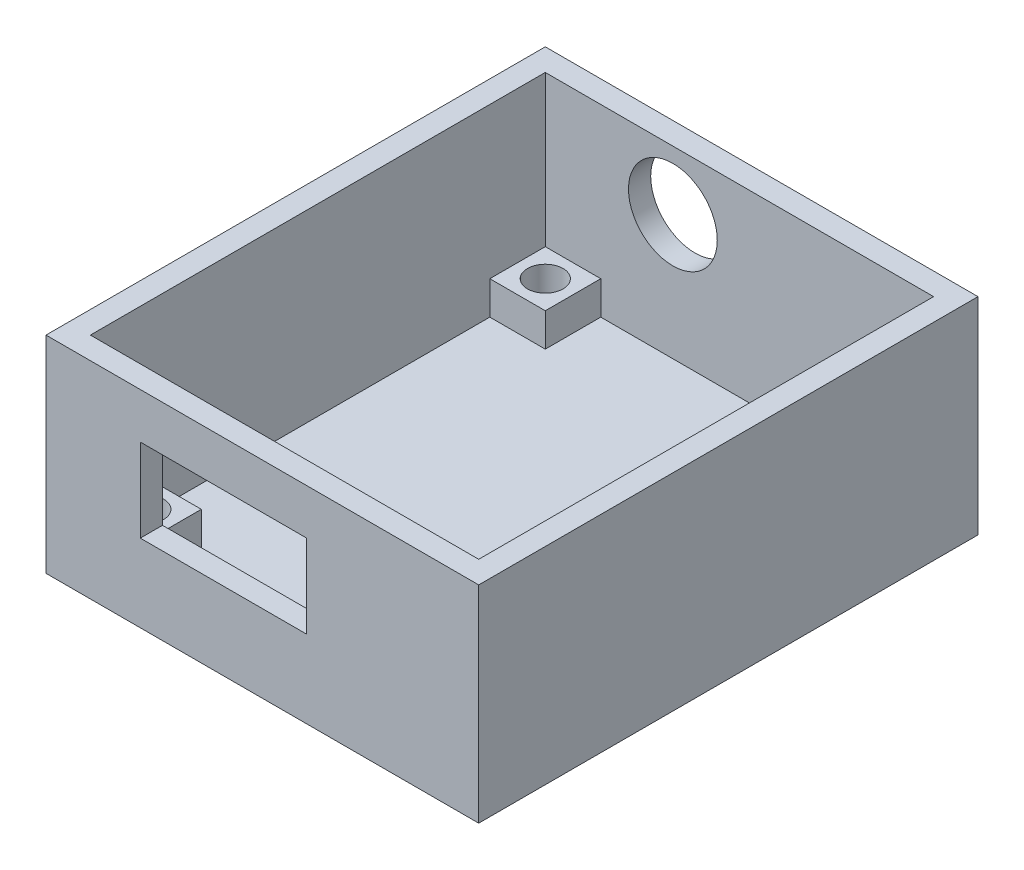
SolidWorks part; units mm, degrees
ref_plane "Front Plane" through (0, 0, 0) normal (0, 0, 1) x (1, 0, 0)
ref_plane "Top Plane" through (0, 0, 0) normal (0, 1, 0) x (1, 0, 0)
ref_plane "Right Plane" through (0, 0, 0) normal (1, 0, 0) x (0, 0, -1)
sketch "Sketch1" plane through (0, 0, 0) normal (0, 1, 0) x (1, 0, 0)
  line L1 (19.5, -22.5) -> (-19.5, -22.5)
  line L2 (19.5, -22.5) -> (19.5, 22.5)
  line L3 (19.5, 22.5) -> (-19.5, 22.5)
  line L4 (-19.5, -22.5) -> (-19.5, 22.5)
  line L5 (19.5, -22.5) -> (-19.5, 22.5) construction
  line L6 (19.5, 22.5) -> (-19.5, -22.5) construction
  point P0 (0, 0)
  dimension "D1" = 45
  dimension "D2" = 39
extrude "Body" add sketch "Sketch1" along normal blind 18.6
shell "Shell1" thickness 2
sketch "Sketch3" plane through (0, 2, 0) normal (0, 1, 0) x (1, 0, 0)
  line L0 (-1000, 0) -> (49000, 0) construction
  line L5 (-17.5, 20.5) -> (-12.5, 20.5)
  line L6 (-17.5, 20.5) -> (-17.5, 15.5)
  line L7 (-17.5, 15.5) -> (-12.5, 15.5)
  line L8 (-12.5, 20.5) -> (-12.5, 15.5)
  line L9 (0, -1000) -> (0, 49000) construction
  line L10 (12.5, 20.5) -> (12.5, 15.5)
  line L11 (17.5, 15.5) -> (12.5, 15.5)
  line L12 (17.5, 20.5) -> (17.5, 15.5)
  line L13 (17.5, 20.5) -> (12.5, 20.5)
  line L14 (17.5, -20.5) -> (12.5, -20.5)
  line L15 (17.5, -20.5) -> (17.5, -15.5)
  line L16 (17.5, -15.5) -> (12.5, -15.5)
  line L17 (12.5, -20.5) -> (12.5, -15.5)
  line L18 (-12.5, -20.5) -> (-12.5, -15.5)
  line L19 (-17.5, -15.5) -> (-12.5, -15.5)
  line L20 (-17.5, -20.5) -> (-17.5, -15.5)
  line L21 (-17.5, -20.5) -> (-12.5, -20.5)
  dimension "D1" = 5
extrude "Inserts_Support" add sketch "Sketch3" along normal blind 3
sketch "Sketch4" plane through (0, 5, 0) normal (0, 1, 0) x (1, 0, 0)
  line L1 (15, -18) -> (-15, -18) construction
  line L2 (15, -18) -> (15, 18) construction
  line L3 (15, 18) -> (-15, 18) construction
  line L4 (-15, -18) -> (-15, 18) construction
  line L5 (15, -18) -> (-15, 18) construction
  line L6 (15, 18) -> (-15, -18) construction
  circle A0 centre (-15, 18) radius 1.6
  circle A1 centre (15, 18) radius 1.6
  circle A2 centre (15, -18) radius 1.6
  circle A3 centre (-15, -18) radius 1.6
  point P0 (0, 0)
  dimension "D3" = 3.2
  dimension "D1" = 30
  dimension "D2" = 36
extrude "Inserts_Holes" cut sketch "Sketch4" against normal blind 4
sketch "Sketch5" plane through (0, 0, 22.5) normal (0, 0, 1) x (1, 0, 0)
  line L0 (-19.5, 18.6) -> (-19.5, 0) construction
  line L1 (-11, 14.5) -> (4, 14.5)
  line L2 (-11, 14.5) -> (-11, 7)
  line L3 (-11, 7) -> (4, 7)
  line L4 (4, 14.5) -> (4, 7)
  line L5 (-11, 14.5) -> (4, 7) construction
  line L6 (-11, 7) -> (4, 14.5) construction
  point P0 (-3.5, 10.75)
  dimension "D1" = 7.5
  dimension "15" = 15
  dimension "D2" = 8.5
  dimension "D3" = 7
extrude "USB_Hole" cut sketch "Sketch5" against normal up to next
sketch "Sketch6" plane through (0, 0, -22.5) normal (0, 0, -1) x (-1, 0, 0)
  line L0 (19.5, 18.6) -> (19.5, 0) construction
  circle A0 centre (6, 13.25) radius 4
  dimension "D1" = 8
  dimension "D2" = 13.25
  dimension "D3" = 13.5
extrude "Jack_Hole" cut sketch "Sketch6" against normal up to next
